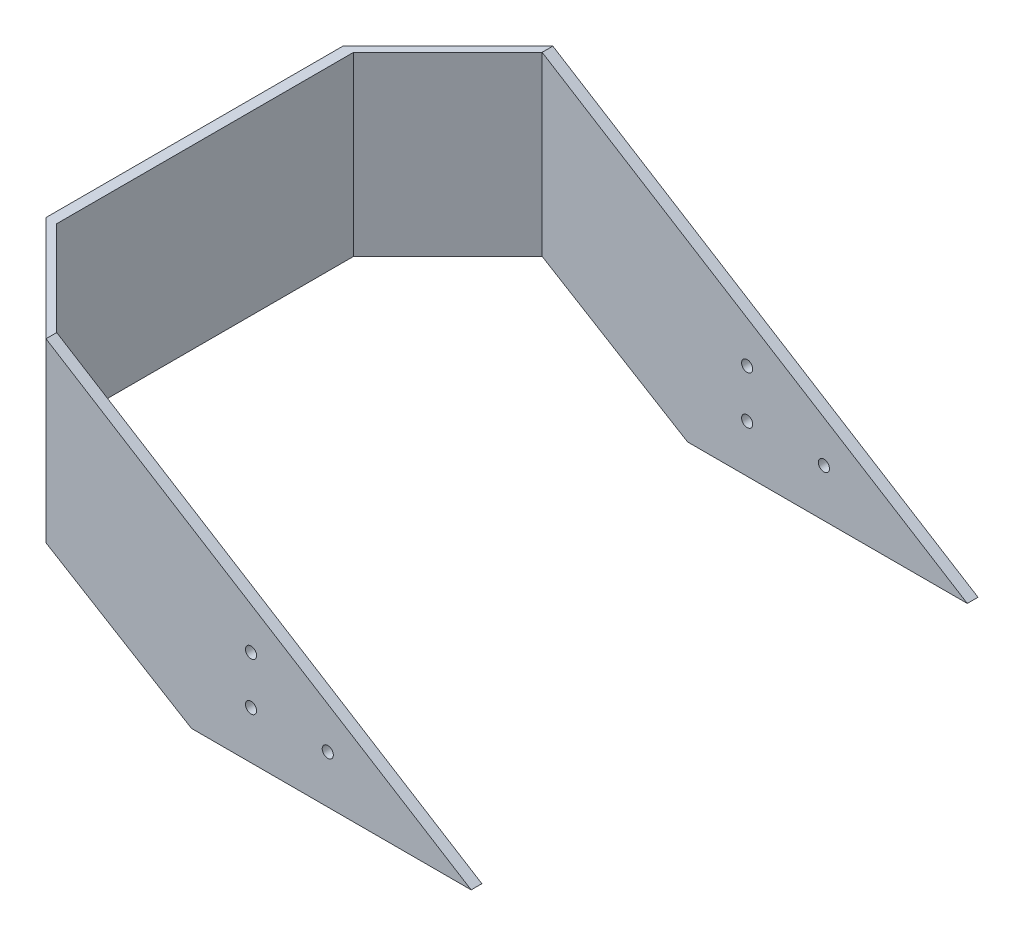
SolidWorks part; units mm, degrees
ref_plane "Front Plane" through (0, 0, 0) normal (0, 0, 1) x (1, 0, 0)
ref_plane "Top Plane" through (0, 0, 0) normal (0, 1, 0) x (1, 0, 0)
ref_plane "Right Plane" through (0, 0, 0) normal (1, 0, 0) x (0, 0, -1)
sketch "Sketch1" plane through (0, 0, 0) normal (0, 1, 0) x (1, 0, 0)
  line L0 (0, 88) -> (0, -88)
  line L1 (0, -88) -> (-103.229, -88)
  line L2 (-103.229, -88) -> (-103.229, 88)
  line L3 (-103.229, 88) -> (0, 88)
  line L4 (-103.229, 0) -> (0, 0)
  line L5 (0, 88) -> (0, 176)
  line L6 (0, 176) -> (-103.229, 176)
  line L7 (-103.229, 176) -> (-103.229, 88)
  line L8 (0, 176) -> (-53.7028, 262.2472)
  line L9 (-53.7028, 262.2472) -> (-156.9318, 262.2472)
  line L10 (-156.9318, 262.2472) -> (-82.5436, 308.5658)
  line L11 (-82.5436, 308.5658) -> (-53.7028, 262.2472)
  line L12 (-82.5436, 308.5658) -> (-156.9318, 428.0339)
  line L13 (-156.9318, 428.0339) -> (-156.9318, 262.2472)
  line L14 (-156.9318, 262.2472) -> (-103.229, 176)
  line L15 (0, -55) -> (0, 55) construction
  line L16 (-55, 0) -> (55, 0) construction
  line L17 (-103.229, -176) -> (-103.229, -88)
  line L18 (-156.9318, -262.2472) -> (-103.229, -176)
  line L19 (-156.9318, -428.0339) -> (-156.9318, -262.2472)
  line L20 (-82.5436, -308.5658) -> (-156.9318, -428.0339)
  line L21 (-82.5436, -308.5658) -> (-53.7028, -262.2472)
  line L22 (-156.9318, -262.2472) -> (-82.5436, -308.5658)
  line L23 (-53.7028, -262.2472) -> (-156.9318, -262.2472)
  line L24 (0, -176) -> (-53.7028, -262.2472)
  line L25 (0, -176) -> (-103.229, -176)
  line L26 (0, -88) -> (0, -176)
  dimension "D1" = 176
  dimension "D2" = 88
  dimension "D3" = 103.229
  dimension "D4" = 87.63
  dimension "D5" = 90
  dimension "D6" = 101.6
sketch "Sketch2" plane through (0, 0, 0) normal (0, 1, 0) x (1, 0, 0)
  line L0 (-314.2569, 88) -> (-314.2569, -88)
  line L1 (-314.2569, -88) -> (-252.0315, -150.2254)
  line L2 (-252.0315, -150.2254) -> (0, -150.2254)
  line L3 (0, -150.2254) -> (0, -143.8754)
  line L4 (0, -143.8754) -> (-252.0315, -143.8754)
  line L5 (-252.0315, -143.8754) -> (-252.0315, -150.2254)
  line L6 (-252.0315, -143.8754) -> (-307.9069, -88)
  line L7 (-307.9069, -88) -> (-314.2569, -88)
  line L8 (-307.9069, -88) -> (-307.9069, 88)
  line L9 (-307.9069, 88) -> (-314.2569, 88)
  line L10 (-314.2569, 88) -> (-252.0315, 150.2254)
  line L11 (-307.9069, 88) -> (-252.0315, 143.8754)
  line L12 (-252.0315, 143.8754) -> (-252.0315, 150.2254)
  line L13 (-252.0315, 150.2254) -> (0, 150.2254)
  line L14 (0, 150.2254) -> (0, 143.8754)
  line L15 (0, 143.8754) -> (-252.0315, 143.8754)
  line L16 (0, -470.8373) -> (0, 470.8373) construction
  line L17 (-86.3125, 0) -> (86.3125, 0) construction
  point P14 (-314.2569, 0)
  dimension "D1" = 6.35
  dimension "D2" = 252.0315
  dimension "D3" = 176
  dimension "D4" = 88
ref_plane "Plane1" through (0, 0, 150.2254) normal (0, 0, 1) x (1, 0, 0)
sketch "Sketch3" plane through (0, 0, 150.2254) normal (0, 0, 1) x (1, 0, 0)
  line L0 (0, 0) -> (-165.7909, 103.228)
  line L1 (-165.7909, 103.228) -> (-165.7909, 0)
  line L2 (-165.7909, 0) -> (-119.4734, 74.3889)
  line L3 (-165.7909, 0) -> (-252.0315, 52.1492)
  line L4 (-252.0315, 0) -> (-252.0315, 166.7676)
  line L5 (-165.7909, 103.228) -> (-252.0315, 156.9248)
  line L6 (-165.7909, 0) -> (0, 0)
  line L7 (0, 0) -> (-39.4847, 0)
  line L8 (-39.4847, 0) -> (-130.4993, 0)
  line L9 (-130.4993, 0) -> (-130.4993, 56.6714)
  line L10 (-130.4993, 56.6714) -> (-39.4847, 0)
  line L11 (-130.4993, 28.3357) -> (-84.992, 28.3357)
  point P14 (0, 0)
  point P16 (0, 0)
  dimension "D1" = 103.228
  dimension "D2" = 87.63
  dimension "D3" = 130.4993
  dimension "D4" = 56.6714
  dimension "D5" = 39.4847
ref_plane "Plane2" through (0, 52.1492, 0) normal (0, 1, 0) x (1, 0, 0)
sketch "Sketch5" plane through (0, 52.1492, 0) normal (0, 1, 0) x (1, 0, 0)
  line L0 (-314.2569, 88) -> (-314.2569, -88)
  line L1 (-314.2569, -88) -> (-252.0315, -150.2254)
  line L2 (-252.0315, -150.2254) -> (0, -150.2254)
  line L3 (0, -150.2254) -> (0, -143.8754)
  line L4 (0, -143.8754) -> (-252.0315, -143.8754)
  line L5 (-252.0315, -143.8754) -> (-252.0315, -150.2254)
  line L6 (-252.0315, -143.8754) -> (-307.9069, -88)
  line L7 (-307.9069, -88) -> (-314.2569, -88)
  line L8 (-307.9069, -88) -> (-307.9069, 88)
  line L9 (-307.9069, 88) -> (-314.2569, 88)
  line L10 (-314.2569, 88) -> (-252.0315, 150.2254)
  line L11 (-307.9069, 88) -> (-252.0315, 143.8754)
  line L12 (-252.0315, 143.8754) -> (-252.0315, 150.2254)
  line L13 (-252.0315, 150.2254) -> (0, 150.2254)
  line L14 (0, 150.2254) -> (0, 143.8754)
  line L15 (0, 143.8754) -> (-252.0315, 143.8754)
extrude "Boss-Extrude1" add sketch "Sketch5" along normal up to vertex (104.7757 mm away) contours L8 L9 L0 L7 | L6 L7 L1 L5 | L11 L12 L10 L9 up to point (-252.0315, 156.9248, 150.2254)
extrude "Boss-Extrude2" add sketch "Sketch3" against normal up to vertex (6.35 mm away) contours L11 L9 L6 L10 | L9 L10 L6 L0 L2 | L1 L2 L0 | L9 L11 L10 | L1 L5 L4 L3
ref_plane "Plane3" through (0, 0, -150.2254) normal (0, 0, 1) x (1, 0, 0)
sketch "Sketch8" plane through (0, 0, -150.2254) normal (0, 0, 1) x (1, 0, 0)
  line L0 (0, 0) -> (-165.7909, 103.228)
  line L1 (-165.7909, 103.228) -> (-165.7909, 0)
  line L2 (-165.7909, 0) -> (-119.4734, 74.3889)
  line L3 (-165.7909, 0) -> (-252.0315, 52.1492)
  line L4 (-252.0315, 0) -> (-252.0315, 166.7676)
  line L5 (-165.7909, 103.228) -> (-252.0315, 156.9248)
  line L6 (-165.7909, 0) -> (0, 0)
  line L7 (0, 0) -> (-39.4847, 0)
  line L8 (-39.4847, 0) -> (-130.4993, 0)
  line L9 (-130.4993, 0) -> (-130.4993, 56.6714)
  line L10 (-130.4993, 56.6714) -> (-39.4847, 0)
  line L11 (-130.4993, 28.3357) -> (-84.992, 28.3357)
  point P2 (0, 0)
  point P14 (0, 0)
  point P16 (0, 0)
extrude "Boss-Extrude3" add sketch "Sketch8" along normal up to vertex (6.35 mm away) contours L1 L5 L4 L3 | L1 L2 L0 | L9 L10 L6 L0 L2 | L11 L9 L6 L10 | L9 L11 L10
sketch "Sketch11" plane through (0, 0, -150.2254) normal (0, 0, 1) x (1, 0, 0)
  line L0 (0, 0) -> (-165.7909, 103.228)
  line L1 (-165.7909, 103.228) -> (-165.7909, 0)
  line L2 (-165.7909, 0) -> (-119.4734, 74.3889)
  line L3 (-165.7909, 0) -> (-252.0315, 52.1492)
  line L4 (-252.0315, 0) -> (-252.0315, 166.7676)
  line L5 (-165.7909, 103.228) -> (-252.0315, 156.9248)
  line L6 (-165.7909, 0) -> (0, 0)
  line L7 (0, 0) -> (-39.4847, 0)
  line L8 (-39.4847, 0) -> (-130.4993, 0)
  line L9 (-130.4993, 0) -> (-130.4993, 56.6714)
  line L10 (-130.4993, 56.6714) -> (-39.4847, 0)
  line L11 (-130.4993, 28.3357) -> (-84.992, 28.3357)
  point P9 (-130.4993, 28.3357)
  point P12 (-130.4993, 56.6714)
  point P13 (-84.992, 28.3357)
sketch "Sketch12" plane through (0, 0, 150.2254) normal (0, 0, 1) x (1, 0, 0)
  line L0 (0, 0) -> (-165.7909, 103.228)
  line L1 (-165.7909, 103.228) -> (-165.7909, 0)
  line L2 (-165.7909, 0) -> (-119.4734, 74.3889)
  line L3 (-165.7909, 0) -> (-252.0315, 52.1492)
  line L4 (-252.0315, 0) -> (-252.0315, 166.7676)
  line L5 (-165.7909, 103.228) -> (-252.0315, 156.9248)
  line L6 (-165.7909, 0) -> (0, 0)
  line L7 (0, 0) -> (-39.4847, 0)
  line L8 (-39.4847, 0) -> (-130.4993, 0)
  line L9 (-130.4993, 0) -> (-130.4993, 56.6714)
  line L10 (-130.4993, 56.6714) -> (-39.4847, 0)
  line L11 (-130.4993, 28.3357) -> (-84.992, 28.3357)
  point P9 (-130.4993, 28.3357)
  point P12 (-130.4993, 56.6714)
  point P13 (-84.992, 28.3357)
hole_wizard "M6 Clearance Hole5" positions "Sketch11" profile "Sketch17" hole size "M6" standard "ANSI Metric"
sketch "Sketch17" plane through (-84.992, 28.3357, -150.2254) normal (1, 0, 0) x (0, 1, 0)
  line L0 (0, 0) -> (0, 6.35)
  line L1 (0, 6.35) -> (3.3, 6.35)
  line L2 (3.3, 6.35) -> (3.3, 0)
  line L5 (3.3, 0) -> (0, 0)
  line L11 (0, -6.35) -> (0, 107.95) construction
  dimension "Thru Hole Dia." = 6.6
  dimension "Thru Hole Depth" = 6.35
hole_wizard "M6 Clearance Hole4" positions "Sketch12" profile "Sketch18" hole size "M6" standard "ANSI Metric" end condition up to next
sketch "Sketch18" plane through (-84.992, 28.3357, 150.2254) normal (1, 0, 0) x (0, -1, 0)
  line L0 (0, 0) -> (0, 6.35)
  line L1 (0, 6.35) -> (3.3, 6.35)
  line L2 (3.3, 6.35) -> (3.3, 0)
  line L5 (3.3, 0) -> (0, 0)
  line L11 (0, -6.35) -> (0, 107.95) construction
  dimension "Thru Hole Dia." = 6.6
  dimension "Thru Hole Depth" = 6.35
equation "\"sidewidth\"= 88mm'so that all three sides are identical while the total width is about 300mm"
equation "\"sideparallelextrusion\"= 4in"
